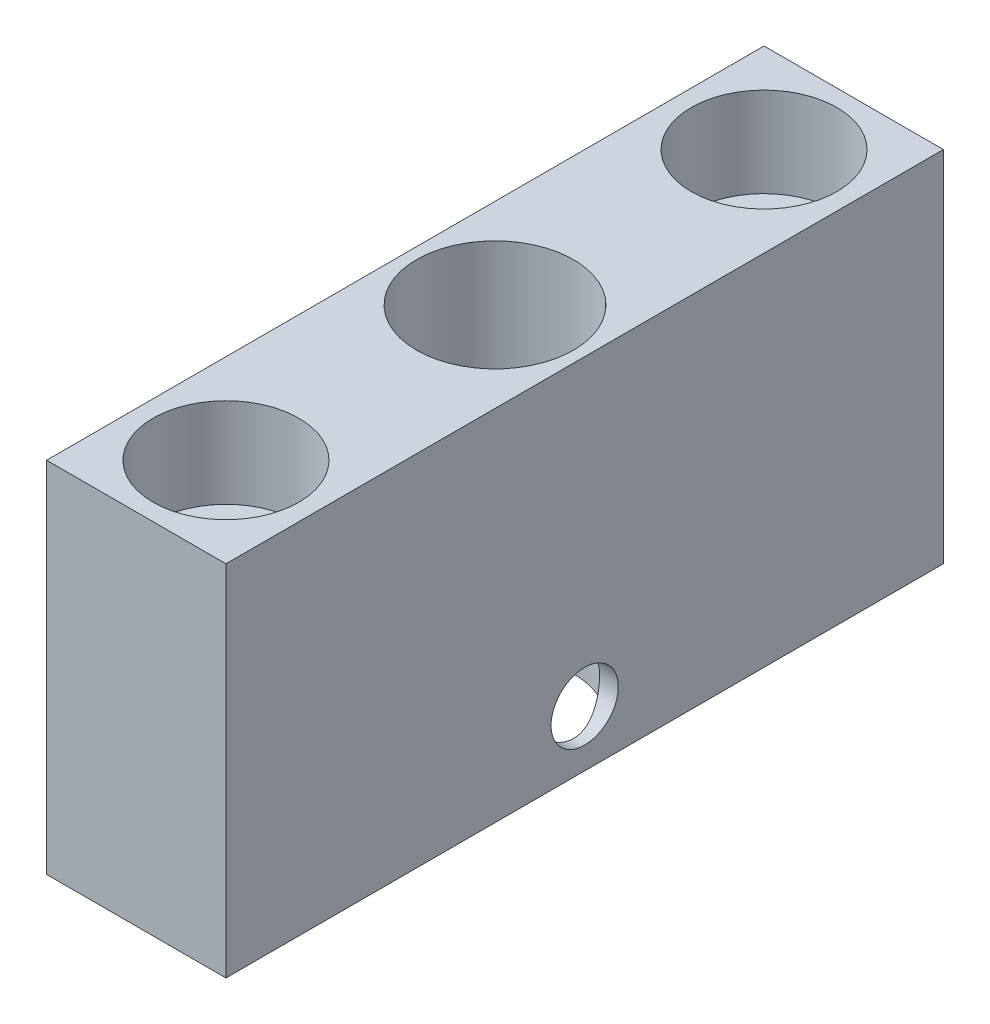
SolidWorks part; units mm, degrees
ref_plane "Front Plane" through (0, 0, 0) normal (0, 0, 1) x (1, 0, 0)
ref_plane "Top Plane" through (0, 0, 0) normal (0, 1, 0) x (1, 0, 0)
ref_plane "Right Plane" through (0, 0, 0) normal (1, 0, 0) x (0, 0, -1)
sketch "Sketch1" plane through (0, 0, 0) normal (1, 0, 0) x (0, 0, -1)
  line L1 (0, 0) -> (101.6, 0)
  line L2 (0, 0) -> (0, 50.8)
  line L3 (0, 50.8) -> (101.6, 50.8)
  line L4 (101.6, 0) -> (101.6, 50.8)
  dimension "D1" = 101.6
  dimension "D2" = 50.8
extrude "Boss-Extrude1" add sketch "Sketch1" along normal blind 25.4
sketch "Sketch2" plane through (0, 50.8, 0) normal (0, 1, 0) x (1, 0, 0)
  line L0 (0, 50.8) -> (25.4, 50.8) construction
  line L1 (0, 101.6) -> (0, 0) construction
  line L2 (25.4, 101.6) -> (25.4, 0) construction
  circle A0 centre (12.7, 50.8) radius 11.1125
  dimension "D1" = 22.225
extrude "Cut-Extrude1" cut sketch "Sketch2" against normal blind 50.8
hole_wizard "CBORE for 1/2 Socket Head Cap Screw1" positions "Sketch6" profile "Sketch7" counterbore size "1/2" standard "ANSI Inch"
sketch "Sketch6" plane through (0, 50.8, 0) normal (0, 1, 0) x (1, 0, 0)
  line L0 (12.7, 101.6) -> (12.7, 0) construction
  line L1 (25.4, 101.6) -> (0, 101.6) construction
  line L2 (25.4, 0) -> (0, 0) construction
  line L3 (0, 50.8) -> (25.4, 50.8) construction
  line L6 (25.4, 101.6) -> (25.4, 0) construction
  line L7 (0, 101.6) -> (0, 0) construction
  point P0 (12.7, 88.9)
  point P2 (12.7, 12.7)
  point P19 (0, 0)
  point P22 (0, 0)
  point P23 (0, 0)
  point P26 (0, 0)
  point P27 (0, 0)
  dimension "D1" = 76.2
  dimension "D2" = 38.1
sketch "Sketch7" plane through (12.7, 50.8, -88.9) normal (1, 0, 0) x (0, 0, 1)
  line L0 (0, 0) -> (0, 54.8535)
  line L1 (0, 54.8535) -> (6.7462, 50.8)
  line L2 (6.7462, 50.8) -> (6.7462, 12.7)
  line L3 (6.7462, 12.7) -> (10.3187, 12.7)
  line L4 (10.3187, 12.7) -> (10.3187, 0)
  line L5 (10.3187, 0) -> (0, 0)
  line L10 (0, 54.8535) -> (-6.7462, 50.8) construction
  line L11 (0, -6.35) -> (0, 107.95) construction
  dimension "Hole Dia." = 13.4925
  dimension "Hole Depth" = 50.8
  dimension "C'Bore Dia." = 20.6375
  dimension "C'Bore Depth" = 12.7
  dimension "Drill Angle" = 118
sketch "Sketch8" plane through (0, 0, 0) normal (-1, 0, 0) x (0, 0, 1)
  line L0 (-50.8, 0) -> (-50.8, 50.8) construction
  line L1 (0, 0) -> (-101.6, 0) construction
  line L2 (-101.6, 50.8) -> (0, 50.8) construction
  circle A0 centre (-50.8, 7.9375) radius 4.7625
  dimension "D1" = 9.525
  dimension "D2" = 7.9375
extrude "Cut-Extrude2" cut sketch "Sketch8" against normal through all
